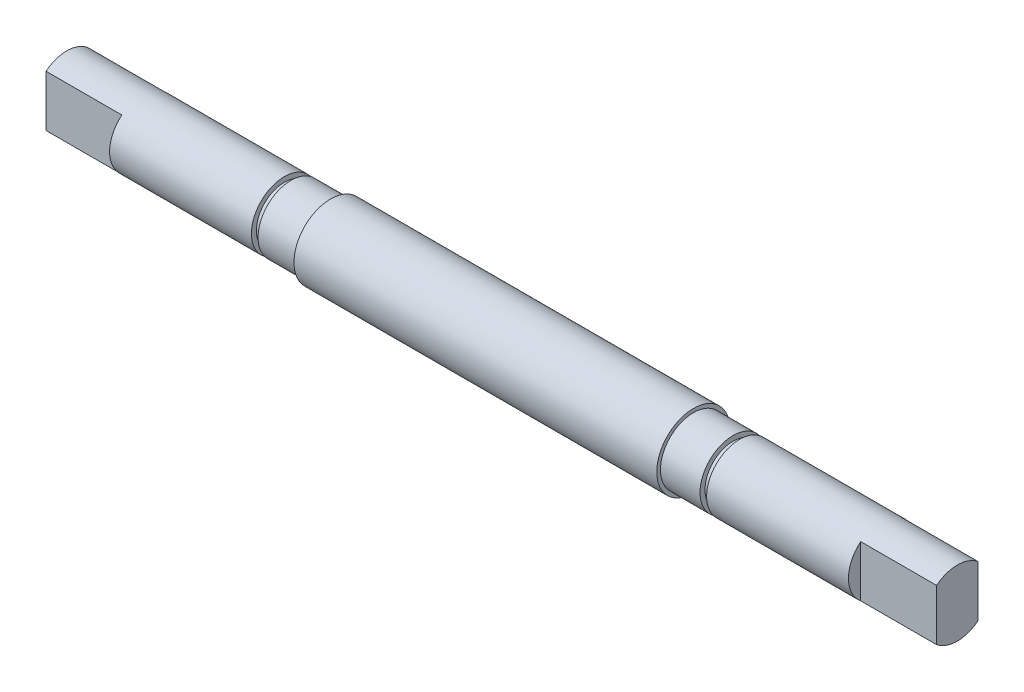
SolidWorks part; units mm, degrees
material "AISI 1020"
ref_plane "Alzado" through (0, 0, 0) normal (0, 0, 1) x (1, 0, 0)
ref_plane "Planta" through (0, 0, 0) normal (0, 1, 0) x (1, 0, 0)
ref_plane "Vista lateral" through (0, 0, 0) normal (1, 0, 0) x (0, 0, -1)
sketch "Croquis1" plane through (0, 0, 0) normal (0, 0, 1) x (1, 0, 0)
  line L0 (70.415, 0) -> (-86.7394, 0) construction
  line L1 (13.5052, 11.1125) -> (68.5052, 11.1125)
  line L2 (13.5052, 11.1125) -> (13.5052, 10)
  line L3 (13.5052, 10) -> (1.5052, 10)
  line L4 (-66.4948, 10) -> (-66.4948, 0)
  line L5 (68.5052, 11.1125) -> (68.5052, 0)
  line L6 (68.5052, 0) -> (-66.4948, 0)
  line L7 (-0.4948, 10) -> (-66.4948, 10)
  line L8 (70.415, 0) -> (-148.7998, 0) construction
  line L9 (-0.4948, 10) -> (-0.4948, 8.5)
  line L10 (-0.4948, 8.5) -> (1.5052, 8.5)
  line L11 (1.5052, 10) -> (1.5052, 8.5)
  dimension "D1" = 22.225
  dimension "D2" = 55
  dimension "D3" = 10
  dimension "D4" = 2
  dimension "D5" = 12
  dimension "D6" = 80
  dimension "D7" = 1.5
revolve "Revolución1" add sketch "Croquis1" angle 360 about L0
sketch "Croquis2" plane through (-66.4948, 0, 0) normal (-1, 0, 0) x (0, 0, 1)
  line L2 (-6.2784, -7.7835) -> (-6.2784, 7.7835)
  line L4 (6.2784, -7.7835) -> (6.2784, 7.7835)
  line L5 (-6.2784, -7.7835) -> (6.2784, 7.7835) construction
  line L6 (-6.2784, 7.7835) -> (6.2784, -7.7835) construction
  circle A0 centre (0, 0) radius 10 construction
  arc A1 (-6.2784, 7.7835) -> (-6.2784, -7.7835) centre (0, 0) ccw
  arc A2 (6.2784, -7.7835) -> (6.2784, 7.7835) centre (0, 0) ccw
  point P0 (0, 0)
  dimension "D1" = 12.5567
extrude "Cortar-Extruir1" cut sketch "Croquis2" against normal blind 23
mirror "Simetría2" about plane through (68.5052, 11.1125, 0) normal (1, 0, 0) of "Cortar-Extruir1", "Revolución1"
